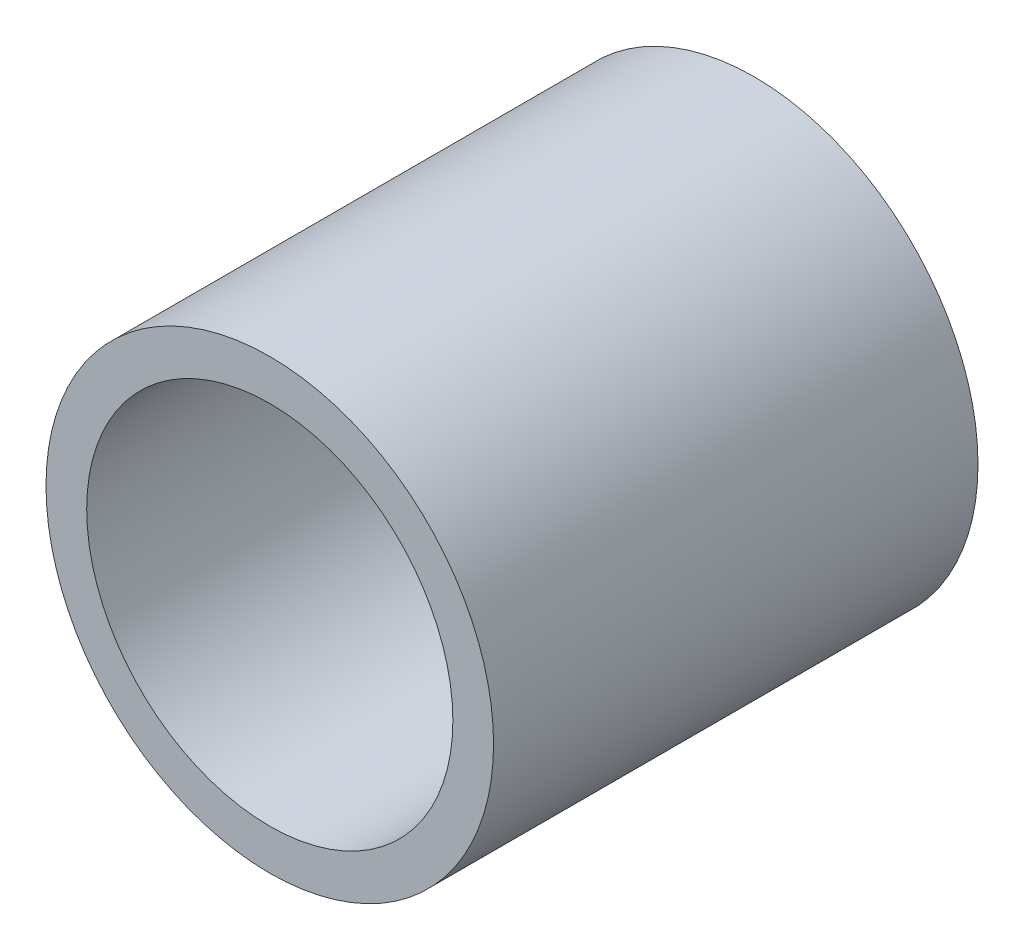
SolidWorks part; units mm, degrees
material "Bronce fosfórico 10% D, UNS C52400"
ref_plane "Alzado" through (0, 0, 0) normal (0, 0, 1) x (1, 0, 0)
ref_plane "Planta" through (0, 0, 0) normal (0, 1, 0) x (1, 0, 0)
ref_plane "Vista lateral" through (0, 0, 0) normal (1, 0, 0) x (0, 0, -1)
sketch "Croquis1" plane through (0, 0, 0) normal (1, 0, 0) x (0, 0, -1)
  line L0 (0, 0) -> (64.9693, 0) construction
  line L1 (0, 0) -> (0, 11)
  line L2 (0, 11) -> (23.812, 11)
  line L3 (23.812, 11) -> (23.812, 0)
  line L4 (23.812, 0) -> (0, 0)
  dimension "D1" = 22
  dimension "D2" = 23.812
revolve "Revolución1" add sketch "Croquis1" angle 360 about L0
sketch "Croquis2" plane through (0, 0, 0) normal (0, 0, 1) x (1, 0, 0)
  circle A0 centre (0, 0) radius 9
  dimension "D1" = 18
extrude "Cortar-Extruir1" cut sketch "Croquis2" against normal up to next
